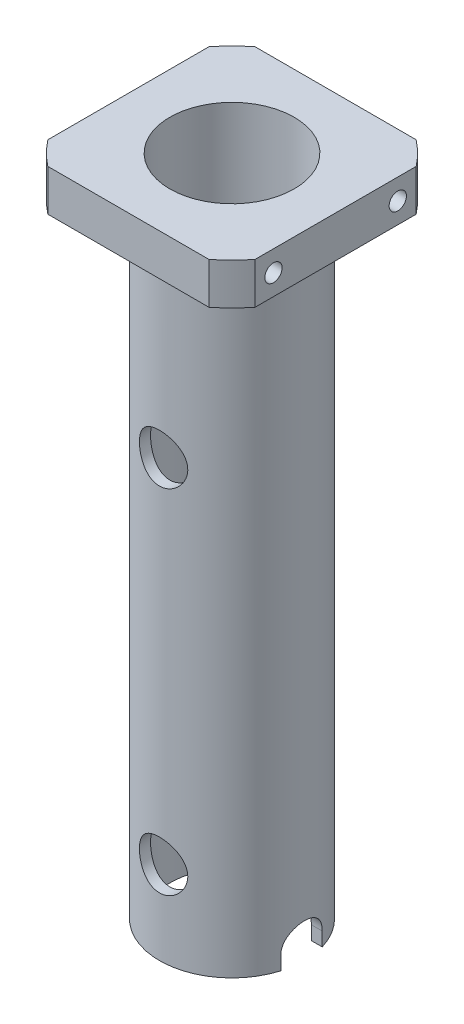
SolidWorks part; units mm, degrees
material "6061-T6 (SS)"
ref_plane "前视基准面" through (0, 0, 0) normal (0, 0, 1) x (1, 0, 0)
ref_plane "上视基准面" through (0, 0, 0) normal (0, 1, 0) x (1, 0, 0)
ref_plane "右视基准面" through (0, 0, 0) normal (1, 0, 0) x (0, 0, -1)
sketch "草图1" plane through (0, 0, 0) normal (0, 1, 0) x (1, 0, 0)
  circle A0 centre (0, 0) radius 10.5
  circle A1 centre (0, 0) radius 9
  dimension "D1" = 21
  dimension "D2" = 18
extrude "凸台-拉伸1" add sketch "草图1" along normal blind 90
ref_plane "基准面1" through (10.5, 0, 0) normal (1, 0, 0) x (0, 0, -1)
sketch "草图3" plane through (10.5, 0, 0) normal (1, 0, 0) x (0, 0, -1)
  line L0 (-3, 0) -> (-3, 2)
  line L1 (-10.5, 0) -> (10.5, 0) construction
  line L2 (3, 2) -> (3, 0)
  line L3 (3, 0) -> (-3, 0)
  arc A0 (-3, 2) -> (3, 2) centre (0, 2) cw
  dimension "D2" = 3
  dimension "D1" = 2
extrude "切除-拉伸1" cut sketch "草图3" against normal up to next
ref_plane "基准面2" through (0, 0, -10.5) normal (0, 0, -1) x (-1, 0, 0)
sketch "草图4" plane through (0, 0, -10.5) normal (0, 0, -1) x (-1, 0, 0)
  line L0 (0, 0) -> (0, 63) construction
  circle A0 centre (0, 63) radius 3.5
  circle A1 centre (0, 12) radius 3.5
  dimension "D3" = 7
  dimension "D1" = 63
  dimension "D2" = 12
extrude "切除-拉伸2" cut sketch "草图4" against normal through all
sketch "草图5" plane through (0, 90, 0) normal (0, 1, 0) x (1, 0, 0)
  line L0 (11.6619, 15) -> (-11.6619, 15)
  line L1 (-15, -11.6619) -> (-15, 11.6619)
  line L2 (15, -11.6619) -> (15, 11.6619)
  line L3 (-15, 0) -> (15, 0) construction
  line L4 (-11.6619, -15) -> (11.6619, -15)
  circle A0 centre (0, 0) radius 9
  arc A1 (15, 11.6619) -> (11.6619, 15) centre (0, 0) ccw
  circle A2 centre (0, 0) radius 9 construction
  arc A3 (-15, -11.6619) -> (-11.6619, -15) centre (0, 0) ccw
  arc A4 (-11.6619, 15) -> (-15, 11.6619) centre (0, 0) ccw
  arc A5 (11.6619, -15) -> (15, -11.6619) centre (0, 0) ccw
  point P14 (0, 0)
  dimension "D1" = 38
  dimension "D2" = 30
  dimension "D3" = 30
extrude "凸台-拉伸2" add sketch "草图5" along normal blind 6
hole_wizard "M3 螺纹孔1" positions "草图6" profile "草图7" tap size "M3" standard "GB"
sketch "草图6" plane through (15, 0, 0) normal (1, 0, 0) x (0, 0, -1)
  line L0 (0, 96) -> (0, 90) construction
  line L1 (-11.6619, 96) -> (11.6619, 96) construction
  line L2 (-10.5, 90) -> (10.5, 90) construction
  point P0 (-9, 93)
  point P2 (9, 93)
  dimension "D1" = 18
  dimension "D2" = 3
cosmetic thread "孔螺蚊线1" parameters "D1"=3.5, "D2"=3
cosmetic thread "孔螺蚊线2" parameters "D1"=3.5, "D2"=3
sketch "草图7" plane through (15, 93, 9) normal (0, 1, 0) x (0, 0, -1)
  line L0 (0, 0) -> (0, 8.7511)
  line L1 (0, 8.7511) -> (1.25, 8)
  line L2 (1.25, 8) -> (1.25, 0)
  line L5 (1.25, 0) -> (0, 0)
  line L10 (0, 8.7511) -> (-1.25, 8) construction
  line L11 (0, -6.35) -> (0, 107.95) construction
  dimension "螺纹孔钻头直径" = 2.5
  dimension "螺纹孔钻头深度" = 8
  dimension "导头角度" = 118
hole_wizard "M3 螺纹孔2" positions "草图8" profile "草图9" tap size "M3" standard "GB"
sketch "草图8" plane through (-15, 0, 0) normal (-1, 0, 0) x (0, 0, 1)
  line L0 (-9, 93) -> (9, 93) construction
  line L2 (-11.6619, 96) -> (11.6619, 96) construction
  point P0 (-9, 93)
  point P2 (9, 93)
  point P9 (0, 93)
  dimension "D1" = 18
  dimension "D2" = 3
sketch "草图9" plane through (-15, 93, -9) normal (0, 1, 0) x (0, 0, 1)
  line L0 (0, 0) -> (0, 8.7511)
  line L1 (0, 8.7511) -> (1.25, 8)
  line L2 (1.25, 8) -> (1.25, 0)
  line L5 (1.25, 0) -> (0, 0)
  line L10 (0, 8.7511) -> (-1.25, 8) construction
  line L11 (0, -6.35) -> (0, 107.95) construction
  dimension "螺纹孔钻头直径" = 2.5
  dimension "螺纹孔钻头深度" = 8
  dimension "导头角度" = 118
cosmetic thread "孔螺蚊线3" parameters "D1"=3.5, "D2"=3
cosmetic thread "孔螺蚊线4" parameters "D1"=3.5, "D2"=3
